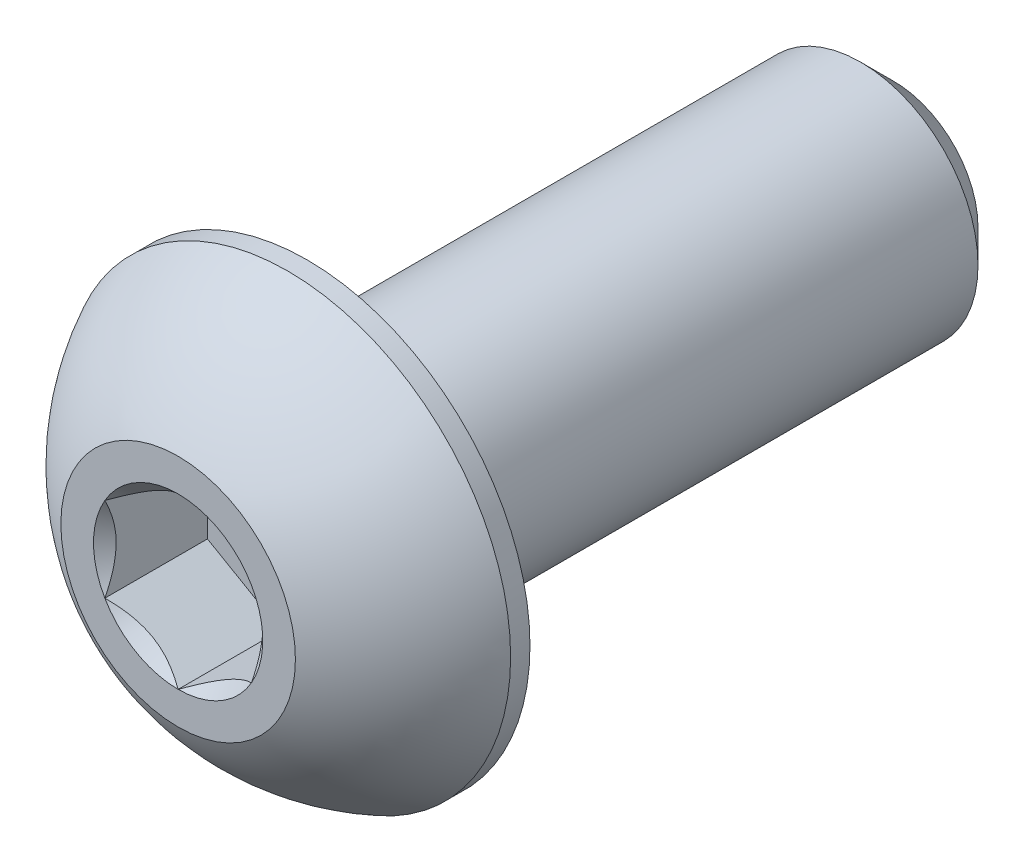
SolidWorks part; units mm, degrees
ref_plane "Front Plane" through (0, 0, 0) normal (0, 0, 1) x (1, 0, 0)
ref_plane "Top Plane" through (0, 0, 0) normal (0, 1, 0) x (1, 0, 0)
ref_plane "Right Plane" through (0, 0, 0) normal (1, 0, 0) x (0, 0, -1)
sketch "Sketch1" plane through (0, 0, 0) normal (1, 0, 0) x (0, 0, -1)
  line L0 (-6.1, 0) -> (6.1, 0) construction
  line L1 (-3.9, 3.8) -> (-3.9, -3.8) construction
  line L2 (6.1, 2) -> (6.1, -2) construction
  line L3 (6.0563, 2.0758) -> (6.4063, 1.4696) construction
  line L4 (6.4063, 1.4696) -> (6.7563, 2.0758) construction
  line L5 (6.7563, 2.0758) -> (6.0563, 2.0758) construction
  line L6 (6.1, 2) -> (6.7125, 2) construction
  line L7 (6.4063, 2.0758) -> (6.4063, 2) construction
  line L8 (6.4063, 2) -> (6.4063, 1.5453) construction
  line L9 (6.4063, 1.5453) -> (6.4063, 1.4696) construction
  line L10 (6.3625, 1.5453) -> (6.45, 1.5453)
  line L11 (6.0781, 2.0379) -> (6.7344, 2.0379)
  line L12 (6.45, 1.5453) -> (6.7344, 2.0379)
  line L13 (6.3625, 1.5453) -> (6.0781, 2.0379)
  line L14 (-6.1, 1.25) -> (-6.1, -1.25) construction
  line L15 (6.1, 2) -> (-3.9, 2) construction
  point P3 (-3.9, 0)
  point P6 (-4.35, 0)
  point P21 (6.4063, 2.0379)
  point P24 (-4.23, 3.8)
  point P25 (4.35, -2)
  point P26 (-6.1, 2)
  dimension "Head Height" = 2.2
  dimension "Length" = 10
  dimension "Head Dia" = 7.6
  dimension "Thread Dia" = 4
  dimension "Pitch" = 0.7
  dimension "D2" = 0.0875
  dimension "Drive Size" = 2.5
  dimension "D1" = 1.75
  dimension "D3" = 0.33
  dimension "D4" = 1.75
sketch "Sketch2" plane through (0, 0, 0) normal (1, 0, 0) x (0, 0, -1)
  line L0 (-6.1, 0) -> (6.1, 0)
  line L1 (6.1, 0) -> (6.1, 1.44)
  line L2 (6.1, 2) -> (6.1, -2) construction
  line L3 (6.1, 1.44) -> (5.54, 2)
  line L4 (5.54, 2) -> (-3.9, 2)
  line L5 (-3.9, 3.8) -> (-3.9, -3.8) construction
  line L6 (-3.9, 2) -> (-3.9, 3.8)
  line L7 (-3.9, 3.8) -> (-4.23, 3.8)
  line L8 (6.1, 2) -> (6.7125, 2) construction
  line L9 (-6.1, 0) -> (-6.1, 2)
  arc A0 (-6.1, 2) -> (-4.23, 3.8) centre (-2.3736, 0) cw
  dimension "D1" = 0.56
  dimension "D2" = 45
revolve "Revolve1" add sketch "Sketch2" angle 360 about L0
sketch "Sketch3" plane through (0, 0, 6.1) normal (0, 0, 1) x (1, 0, 0)
  line L1 (0, 1.4434) -> (-1.25, 0.7217)
  line L2 (-1.25, 0.7217) -> (-1.25, -0.7217)
  line L3 (-1.25, -0.7217) -> (0, -1.4434)
  line L4 (0, -1.4434) -> (1.25, -0.7217)
  line L5 (1.25, -0.7217) -> (1.25, 0.7217)
  line L6 (1.25, 0.7217) -> (0, 1.4434)
  circle A0 centre (0, 0) radius 1.25 construction
  dimension "D1" = 2.5
extrude "Cut-Extrude1" cut sketch "Sketch3" against normal up to vertex (1.75 mm away) up to point (0, 0, 4.35)
sketch "Sketch4" plane through (0, 0, 6.1) normal (0, 0, 1) x (1, 0, 0)
  circle A0 centre (0, 0) radius 1.4434
extrude "Cut-Extrude2" cut sketch "Sketch4" against normal blind 10 draft 45
equation "\"D2@Sketch1\" = \"Pitch@Sketch1\" / 8"
equation "\"D1@Sketch1\"=\"Drive Size@Sketch1\"*.7"
equation "\"D3@Sketch1\"=\"Head Height@Sketch1\"*.15"
equation "\"D1@Sketch2\"=\"Pitch@Sketch1\"*.8"
equation "\"D1@Sketch3\"=\"Drive Size@Sketch1\""
equation "\"D4@Sketch1\"=\"Pitch@Sketch1\"*2.5"
